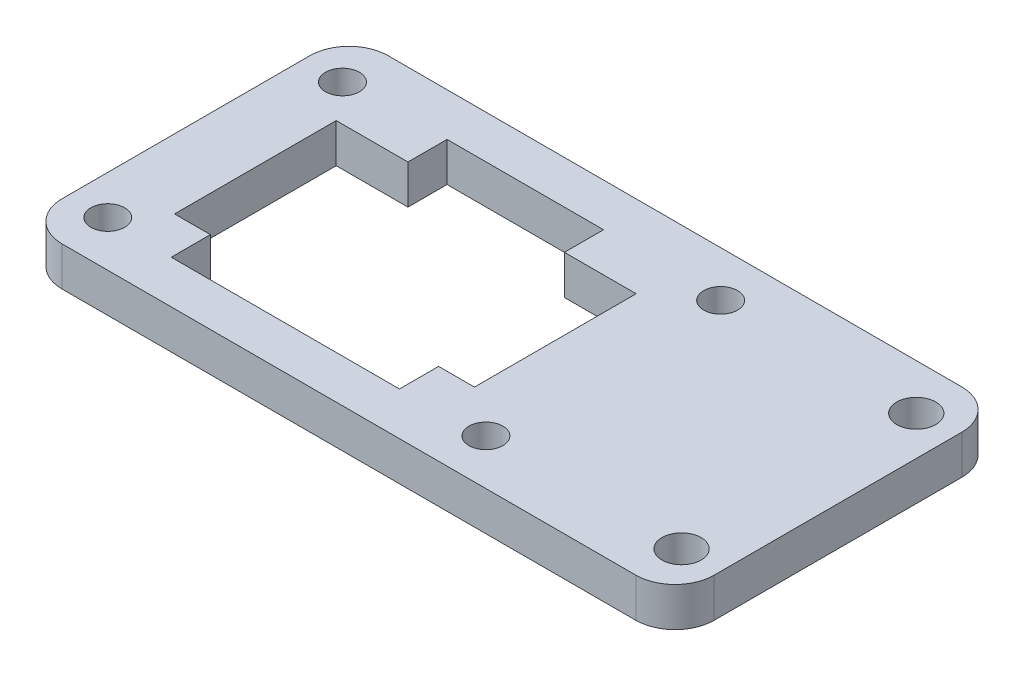
SolidWorks part; units mm, degrees
material "Acrílico (médio-alto impacto)"
ref_plane "Plano frontal" through (0, 0, 0) normal (0, 0, 1) x (1, 0, 0)
ref_plane "Plano superior" through (0, 0, 0) normal (0, 1, 0) x (1, 0, 0)
ref_plane "Plano direito" through (0, 0, 0) normal (1, 0, 0) x (0, 0, -1)
sketch "Perfil Principal" plane through (0, 0, 0) normal (0, 1, 0) x (1, 0, 0)
  line L1 (-25, -12.5) -> (25, -12.5)
  line L2 (-25, -12.5) -> (-25, 12.5)
  line L3 (-25, 12.5) -> (25, 12.5)
  line L4 (25, -12.5) -> (25, 12.5)
  line L5 (0, 12.5) -> (0, -12.5) construction
  line L6 (-25, 0) -> (25, 0) construction
  point P0 (0, 0)
  dimension "D1" = 50
  dimension "D2" = 25
sketch "Posições Furos" plane through (0, 0, 0) normal (0, 1, 0) x (1, 0, 0)
  line L0 (-25, 0) -> (25, 0) construction
  line L1 (-22, 9) -> (7, 9) construction
  line L2 (-22, 9) -> (-22, -9) construction
  line L3 (-22, -9) -> (7, -9) construction
  line L4 (7, 9) -> (7, -9) construction
  line L5 (-7.5, -9) -> (-7.5, 9) construction
  line L6 (-22, 0) -> (7, 0) construction
  line L7 (25, -12.5) -> (25, 12.5) construction
  line L8 (22, 9) -> (7, 9) construction
  line L9 (22, 9) -> (22, -9) construction
  line L10 (22, -9) -> (7, -9) construction
  line L11 (7, 9) -> (7, -9) construction
  line L12 (14.5, -9) -> (14.5, 9) construction
  line L13 (22, 0) -> (7, 0) construction
  line L14 (-25, -12.5) -> (-25, 12.5) construction
  point P0 (-7.5, 0)
  point P6 (14.5, 0)
  dimension "D1" = 18
  dimension "D2" = 29
  dimension "D3" = 3
  dimension "D4" = 3
  dimension "D5" = 15
extrude "Base" add sketch "Perfil Principal" along normal blind 3 contours L2 L3 L4 L1
sketch "Perfil Corte" plane through (49.188, 0, 22.1168) normal (0, -1, 0) x (-1, 0, 0)
  line L0 (57.368, 12.1168) -> (57.368, 32.1168) construction
  line L1 (45.868, 15.9168) -> (68.868, 15.9168)
  line L2 (45.868, 15.9168) -> (45.868, 28.3168)
  line L3 (45.868, 28.3168) -> (68.868, 28.3168)
  line L4 (68.868, 15.9168) -> (68.868, 28.3168)
  line L5 (57.368, 28.3168) -> (57.368, 15.9168) construction
  line L6 (45.868, 22.1168) -> (68.868, 22.1168) construction
  line L7 (68.868, 22.1168) -> (74.188, 22.1168) construction
  line L8 (74.188, 9.6168) -> (74.188, 34.6168) construction
  line L9 (74.188, 34.6168) -> (24.188, 34.6168) construction
  point P0 (57.368, 22.1168)
  point P7 (57.368, 22.1168)
  dimension "D1" = 23
  dimension "entre furos" = 20
  dimension "D2" = 12.4
  dimension "Afastamento Lateral" = 16.82
  dimension "Posicionamento Altura" = 12.5
extrude "Corte Principal" cut sketch "Perfil Corte" against normal through all
sketch "Esboço7" plane through (56.453, 0, 26.4416) normal (0, -1, 0) x (-1, 0, 0)
  line L0 (64.633, 16.4416) -> (64.633, 36.4416) construction
  line L1 (58.633, 35.6416) -> (70.633, 35.6416)
  line L2 (58.633, 35.6416) -> (58.633, 32.6416)
  line L3 (58.633, 32.6416) -> (70.633, 32.6416)
  line L4 (70.633, 35.6416) -> (70.633, 32.6416)
  line L5 (64.633, 32.6416) -> (64.633, 35.6416) construction
  line L6 (58.633, 34.1416) -> (70.633, 34.1416) construction
  line L7 (53.133, 32.6416) -> (76.133, 32.6416) construction
  line L8 (53.133, 20.2416) -> (53.133, 32.6416) construction
  line L9 (53.133, 20.2416) -> (76.133, 20.2416) construction
  line L10 (55.883, 17.2416) -> (73.383, 17.2416)
  line L11 (55.883, 17.2416) -> (55.883, 20.2416)
  line L12 (55.883, 20.2416) -> (73.383, 20.2416)
  line L13 (73.383, 17.2416) -> (73.383, 20.2416)
  line L14 (64.633, 20.2416) -> (64.633, 17.2416) construction
  line L15 (55.883, 18.7416) -> (73.383, 18.7416) construction
  point P0 (64.633, 34.1416)
  point P10 (64.633, 18.7416)
  dimension "D1" = 3
  dimension "D2" = 5.5
  dimension "D3" = 17.5
extrude "Corte-extrusão3" cut sketch "Esboço7" against normal through all
other "Furos Motor<1>"
hole_wizard "Furo de diâmetro Ø3.0 (3)1" positions "Esboço8" profile "Esboço9" hole size "Ø3.0" standard "ISO" end condition through all
sketch "Esboço8" plane through (0, 3, 0) normal (0, 1, 0) x (1, 0, 0)
  point P0 (22, 9)
  point P3 (22, -9)
sketch "Esboço9" plane through (22, 3, -9) normal (1, 0, 0) x (0, 0, 1)
  line L0 (0, 0) -> (0, 3)
  line L1 (0, 3) -> (1.5, 3)
  line L2 (1.5, 3) -> (1.5, 0)
  line L5 (1.5, 0) -> (0, 0)
  line L11 (0, -6.35) -> (0, 107.95) construction
  dimension "Thru Hole Dia." = 3
  dimension "Thru Hole Depth" = 3
hole_wizard "Furo de diâmetro Ø2.6 (2.6)1" positions "Esboço10" profile "Esboço11" hole size "Ø2.6" standard "ISO" end condition through all
sketch "Esboço10" plane through (0, 3, 0) normal (0, 1, 0) x (1, 0, 0)
  point P0 (-22, 9)
  point P3 (-22, -9)
  point P6 (7, 9)
  point P9 (7, -9)
sketch "Esboço11" plane through (-22, 3, -9) normal (1, 0, 0) x (0, 0, 1)
  line L0 (0, 0) -> (0, 3)
  line L1 (0, 3) -> (1.3, 3)
  line L2 (1.3, 3) -> (1.3, 0)
  line L5 (1.3, 0) -> (0, 0)
  line L11 (0, -6.35) -> (0, 107.95) construction
  dimension "Thru Hole Dia." = 2.6
  dimension "Thru Hole Depth" = 3
fillet "Filete1" radius 3 4 edges at (-25, 1.5, -12.5) (25, 1.5, -12.5) (25, 1.5, 12.5) (-25, 1.5, 12.5)
